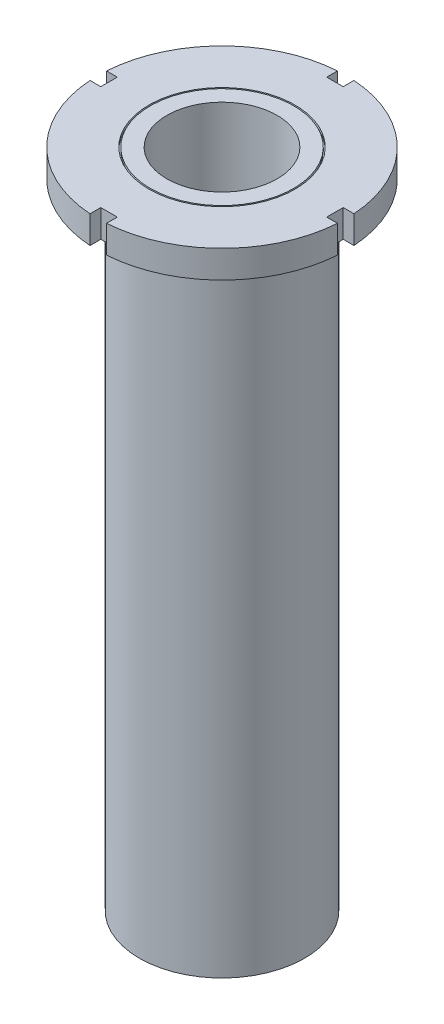
SolidWorks part; units mm, degrees
material "AISI 304"
ref_plane "Front Plane" through (0, 0, 0) normal (0, 0, 1) x (1, 0, 0)
ref_plane "Top Plane" through (0, 0, 0) normal (0, 1, 0) x (1, 0, 0)
ref_plane "Right Plane" through (0, 0, 0) normal (1, 0, 0) x (0, 0, -1)
sketch "Sketch1" plane through (0, 0, 0) normal (0, 1, 0) x (1, 0, 0)
  circle A0 centre (0, 0) radius 15
  dimension "D1" = 30
extrude "Boss-Extrude1" add sketch "Sketch1" along normal blind 115
sketch "Sketch2" plane through (0, 115, 0) normal (0, 1, 0) x (1, 0, 0)
  line L0 (-1.5, 20.5) -> (1.5, 20.5)
  line L1 (0, 20.5) -> (0, -20.5) construction
  line L2 (1.5, 20.5) -> (1.5, 22.4499)
  line L3 (-1.5, 20.5) -> (-1.5, 22.4499)
  line L4 (20.5, 1.5) -> (22.4499, 1.5)
  line L5 (20.5, 1.5) -> (20.5, -1.5)
  line L6 (20.5, -1.5) -> (22.4499, -1.5)
  line L7 (1.5, -20.5) -> (1.5, -22.4499)
  line L8 (1.5, -20.5) -> (-1.5, -20.5)
  line L9 (-1.5, -20.5) -> (-1.5, -22.4499)
  line L10 (-20.5, -1.5) -> (-22.4499, -1.5)
  line L11 (-20.5, -1.5) -> (-20.5, 1.5)
  line L12 (-20.5, 1.5) -> (-22.4499, 1.5)
  arc A0 (-22.4499, -1.5) -> (-1.5, -22.4499) centre (0, 0) ccw
  arc A1 (22.4499, 1.5) -> (1.5, 22.4499) centre (0, 0) ccw
  arc A2 (-1.5, 22.4499) -> (-22.4499, 1.5) centre (0, 0) ccw
  arc A3 (1.5, -22.4499) -> (22.4499, -1.5) centre (0, 0) ccw
  point P6 (0, 0)
  point P9 (0, 20.5)
  point P26 (0, 0)
  dimension "D4" = 1.9499
  dimension "D6" = 3
  dimension "D7" = 1.9499
extrude "Boss-Extrude2" add sketch "Sketch2" along normal blind 5
sketch "Sketch3" plane through (0, 120, 0) normal (0, 1, 0) x (1, 0, 0)
  circle A0 centre (0, 0) radius 13
  circle A1 centre (0, 0) radius 13.25
  dimension "D1" = 26
  dimension "D2" = 26.5
extrude "Cut-Extrude1" cut sketch "Sketch3" against normal blind 0.5
sketch "Sketch4" plane through (0, 120, 0) normal (0, 1, 0) x (1, 0, 0)
  circle A0 centre (0, 0) radius 10
  dimension "D1" = 20
extrude "Cut-Extrude2" cut sketch "Sketch4" against normal through all
sketch "Sketch5" plane through (0, 0, 0) normal (1, 0, 0) x (0, 0, -1)
  circle A0 centre (0, 97.5841) radius 1.5
  dimension "D1" = 3
extrude "Boss-Extrude3" add sketch "Sketch5" along normal mid plane 20.7
sketch "Sketch6" plane through (0, 0, 0) normal (0, -1, 0) x (1, 0, 0)
  point P0 (0, 0)
